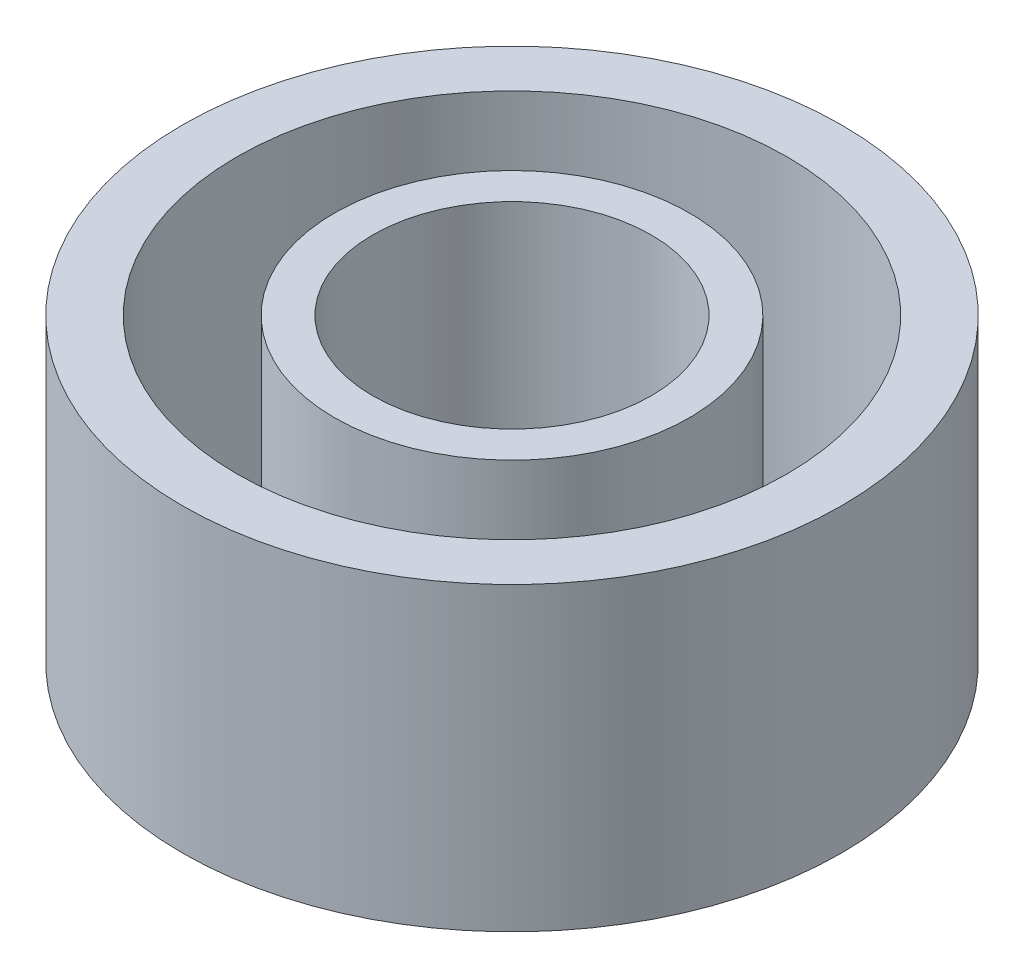
SolidWorks part; units mm, degrees
ref_plane "Front" through (0, 0, 0) normal (0, 0, 1) x (1, 0, 0)
ref_plane "Top" through (0, 0, 0) normal (0, 1, 0) x (1, 0, 0)
ref_plane "Right" through (0, 0, 0) normal (1, 0, 0) x (0, 0, -1)
sketch "Sketch1" plane through (0, 0, 0) normal (0, 1, 0) x (1, 0, 0)
  circle A0 centre (0, 0) radius 2.3241
  circle A1 centre (0, 0) radius 2.9591
  circle A2 centre (0, 0) radius 5.4991
  circle A3 centre (0, 0) radius 4.5847
  dimension "D1" = 4.6482
  dimension "D3" = 10.9982
  dimension "D2" = 0.635
  dimension "D4" = 0.9144
extrude "Boss-Extrude1" add sketch "Sketch1" along normal blind 5.0165 contours A2 A3 | A1 A0
ref_plane "Plane1" through (0, 2.5082, 0) normal (0, 1, 0) x (1, 0, 0)
sketch "Sketch2" plane through (0, 2.5082, 0) normal (0, 1, 0) x (1, 0, 0)
  line L1 (0, 6.0283) -> (0, -5.9658) construction
  point P3 (0, 0)
ref_plane "Plane2" through (0, 2.5082, 0) normal (0, 0, 1) x (1, 0, 0)
sketch "Sketch3" plane through (0, 2.5082, 0) normal (0, 0, 1) x (1, 0, 0)
  line L0 (0, -6.5571) -> (0, 6.5231) construction
ref_plane "Plane3" through (0, 0, 0) normal (-1, 0, 0) x (0, 0, 1)
